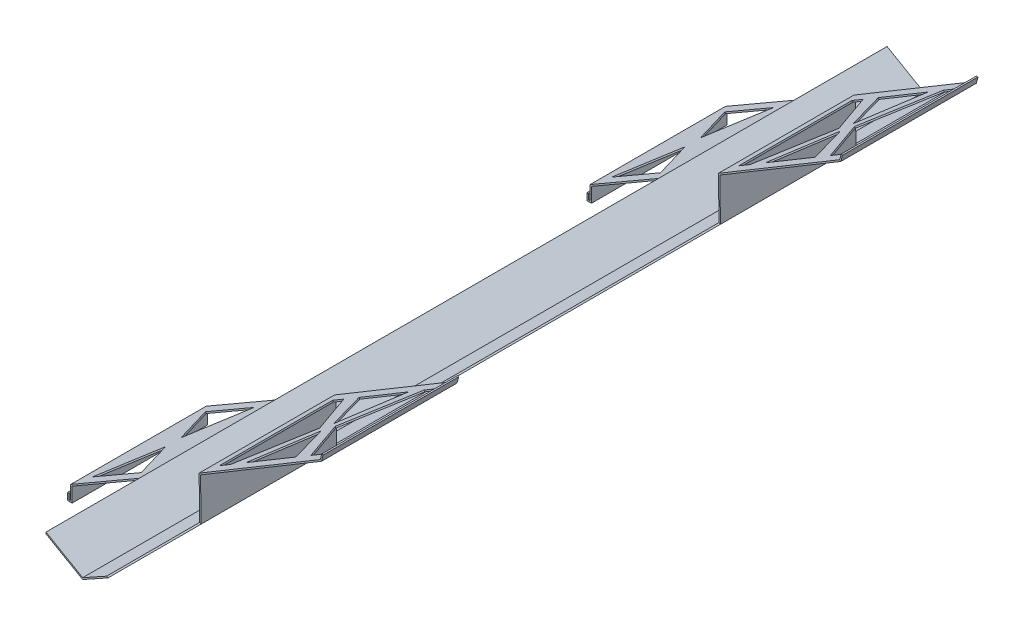
SolidWorks part; units mm, degrees
ref_plane "Front Plane" through (0, 0, 0) normal (0, 0, 1) x (1, 0, 0)
ref_plane "Top Plane" through (0, 0, 0) normal (0, 1, 0) x (1, 0, 0)
ref_plane "Right Plane" through (0, 0, 0) normal (1, 0, 0) x (0, 0, -1)
sketch "Sketch1" plane through (0, 0, 0) normal (0, 0, 1) x (1, 0, 0)
  line L0 (11, 5) -> (11, 55)
  line L1 (11, 55) -> (253.4871, 195)
  line L2 (253.4871, 195) -> (383.3909, 120)
  line L3 (383.3909, 120) -> (468.1313, 167.0572)
  line L4 (468.1313, 167.0572) -> (465.9277, 317.041)
  line L5 (465.9277, 317.041) -> (895.2211, 573.3751)
  line L11 (473.1747, 164.1386) -> (383.343, 114.2542)
  line L12 (383.343, 114.2542) -> (253.4871, 189.2265)
  line L13 (253.4871, 189.2265) -> (16, 52.1132)
  line L14 (16, 52.1132) -> (16, 0)
  line L16 (11, 5) -> (5, 5)
  line L20 (5, 5) -> (5, 25)
  line L21 (5, 25) -> (0, 25)
  line L22 (0, 25) -> (0, 0)
  line L23 (0, 0) -> (16, 0)
  line L24 (470.9696, 314.228) -> (473.1747, 164.1386)
  line L25 (895.2211, 573.3751) -> (900.7371, 593.4071)
  line L26 (900.7371, 593.4071) -> (905.633, 592.3922)
  line L28 (905.633, 592.3922) -> (899.7169, 570.2361)
  line L29 (470.9696, 314.228) -> (899.7169, 570.2361)
  dimension "D1" = 5
  dimension "D2" = 5
  dimension "D3" = 5
  dimension "D4" = 5
  dimension "D5" = 5
  dimension "D6" = 120
  dimension "D7" = 120
  dimension "D8" = 5
  dimension "D9" = 280
  dimension "D10" = 500
  dimension "D11" = 245
  dimension "D12" = 150
  dimension "D13" = 5
  dimension "D14" = 150
  dimension "D15" = 6
  dimension "D16" = 50
  dimension "D17" = 25
  dimension "D18" = 120
extrude "Boss-Extrude1" add sketch "Sketch1" along normal blind 480
sketch "Sketch3" plane through (0, 0, 480) normal (0, 0, 1) x (1, 0, 0)
  line L0 (253.4871, 195) -> (383.3909, 120)
  line L1 (383.3909, 120) -> (468.1313, 167.0572)
  line L5 (473.1747, 164.1386) -> (383.343, 114.2542)
  line L6 (383.343, 114.2542) -> (253.4871, 189.2265)
  line L7 (253.4871, 189.2265) -> (253.4871, 195)
  line L8 (468.1313, 167.0572) -> (473.1747, 164.1386)
extrude "Boss-Extrude2" add sketch "Sketch3" along normal blind 1360 and the other way blind 810
sketch "Sketch4" plane through (0, 0, 1840) normal (0, 0, 1) x (1, 0, 0)
  line L0 (0, 25) -> (5, 25)
  line L1 (5, 25) -> (5, 5)
  line L2 (5, 5) -> (11, 5)
  line L3 (11, 5) -> (11, 55)
  line L4 (11, 55) -> (253.4871, 195)
  line L5 (253.4871, 195) -> (383.3909, 120)
  line L6 (383.3909, 120) -> (468.1313, 167.0572)
  line L7 (468.1313, 167.0572) -> (465.9277, 317.041)
  line L8 (465.9277, 317.041) -> (895.2211, 573.3751)
  line L9 (895.2211, 573.3751) -> (900.7371, 593.4071)
  line L10 (900.7371, 593.4071) -> (905.633, 592.3922)
  line L11 (905.633, 592.3922) -> (899.7169, 570.2361)
  line L12 (899.7169, 570.2361) -> (470.9696, 314.228)
  line L13 (470.9696, 314.228) -> (473.1747, 164.1386)
  line L14 (473.1747, 164.1386) -> (383.343, 114.2542)
  line L15 (383.343, 114.2542) -> (253.4871, 189.2265)
  line L16 (253.4871, 189.2265) -> (16, 52.1132)
  line L17 (16, 52.1132) -> (16, 0)
  line L18 (16, 0) -> (0, 0)
  line L19 (0, 0) -> (0, 25)
extrude "Boss-Extrude3" add sketch "Sketch4" along normal blind 480
sketch "Sketch5" plane through (0, 0, 2320) normal (0, 0, 1) x (1, 0, 0)
  line L0 (253.4871, 195) -> (383.3909, 120)
  line L1 (383.3909, 120) -> (468.1313, 167.0572)
  line L2 (468.1313, 167.0572) -> (473.1747, 164.1386)
  line L3 (473.1747, 164.1386) -> (383.343, 114.2542)
  line L4 (383.343, 114.2542) -> (253.4871, 189.2265)
  line L5 (253.4871, 189.2265) -> (253.4871, 195)
extrude "Boss-Extrude4" add sketch "Sketch5" along normal blind 330
sketch "Sketch8" plane through (-17.0928, 28.626, 0) normal (-0.5127, 0.8586, 0) x (0.8586, 0.5127, 0)
  line L0 (710.0636, -40) -> (915.0888, -40)
  line L2 (812.5762, -217.557) -> (710.0636, -40)
  line L3 (1062.5762, 0) -> (562.5762, 0) construction
  line L4 (812.5762, 53.7156) -> (812.5762, -561.4179) construction
  line L5 (562.5762, -480) -> (562.5762, 0) construction
  line L7 (562.5762, -240) -> (1062.5762, -240) construction
  line L8 (1062.5762, -480) -> (1062.5762, 0) construction
  line L9 (780.5604, -240) -> (647.1054, -39.4975)
  line L10 (647.1054, -39.4975) -> (600.4556, -39.4975)
  line L11 (600.4556, -39.4975) -> (600.4556, -440.5025)
  line L12 (812.5762, -217.557) -> (915.0888, -40)
  line L13 (844.592, -240) -> (978.047, -39.4975)
  line L14 (978.047, -39.4975) -> (1024.6968, -39.4975)
  line L15 (1024.6968, -39.4975) -> (1024.6968, -440.5025)
  line L16 (978.047, -440.5025) -> (1024.6968, -440.5025)
  line L17 (844.592, -240) -> (978.047, -440.5025)
  line L18 (812.5762, -262.443) -> (915.0888, -440)
  line L19 (812.5762, -262.443) -> (710.0636, -440)
  line L20 (710.0636, -440) -> (915.0888, -440)
  line L21 (647.1054, -440.5025) -> (600.4556, -440.5025)
  line L22 (780.5604, -240) -> (647.1054, -440.5025)
  line L29 (80.5575, -440) -> (279.9346, -440)
  line L30 (279.9346, -440) -> (180.246, -267.3344)
  line L31 (180.246, -267.3344) -> (80.5575, -440)
  line L32 (562.5762, -240) -> (37.6412, -240) construction
  line L33 (37.6412, -480) -> (37.6412, 0) construction
  line L34 (80.5575, -40) -> (279.9346, -40)
  line L35 (180.246, -212.6656) -> (80.5575, -40)
  line L36 (279.9346, -40) -> (180.246, -212.6656)
  line L37 (-555.546, -1160) -> (1698.5242, -1160) construction
  line L38 (1062.5762, -480) -> (562.5762, -480) construction
  line L39 (1062.5762, -1840) -> (562.5762, -1840) construction
  line L40 (710.0636, -1880) -> (915.0888, -1880)
  line L41 (812.5762, -2057.557) -> (710.0636, -1880)
  line L42 (812.5762, -2057.557) -> (915.0888, -1880)
  line L43 (978.047, -1879.4975) -> (1024.6968, -1879.4975)
  line L44 (978.047, -2280.5025) -> (1024.6968, -2280.5025)
  line L45 (1024.6968, -2280.5025) -> (1024.6968, -1879.4975)
  line L58 (844.592, -2080) -> (978.047, -2280.5025)
  line L59 (844.592, -2080) -> (978.047, -1879.4975)
  line L60 (812.5762, -2102.443) -> (915.0888, -2280)
  line L61 (710.0636, -2280) -> (915.0888, -2280)
  line L62 (812.5762, -2102.443) -> (710.0636, -2280)
  line L63 (780.5604, -2080) -> (647.1054, -1879.4975)
  line L64 (647.1054, -1879.4975) -> (600.4556, -1879.4975)
  line L65 (600.4556, -2280.5025) -> (600.4556, -1879.4975)
  line L66 (647.1054, -2280.5025) -> (600.4556, -2280.5025)
  line L67 (780.5604, -2080) -> (647.1054, -2280.5025)
  line L68 (80.5575, -1880) -> (279.9346, -1880)
  line L69 (279.9346, -1880) -> (180.246, -2052.6656)
  line L70 (180.246, -2052.6656) -> (80.5575, -1880)
  line L71 (279.9346, -2280) -> (180.246, -2107.3344)
  line L72 (80.5575, -2280) -> (279.9346, -2280)
  line L73 (180.246, -2107.3344) -> (80.5575, -2280)
  point P18 (812.5762, -40)
  point P23 (1024.6968, -240)
  point P29 (600.4556, -240)
  dimension "D1" = 40
  dimension "D2" = 60
  dimension "D3" = 60
  dimension "D4" = 250
  dimension "D5" = 60
  dimension "D6" = 680
  dimension "D7" = 680
extrude "Cut-Extrude1" cut sketch "Sketch8" against normal blind 30 and the other way blind 10
